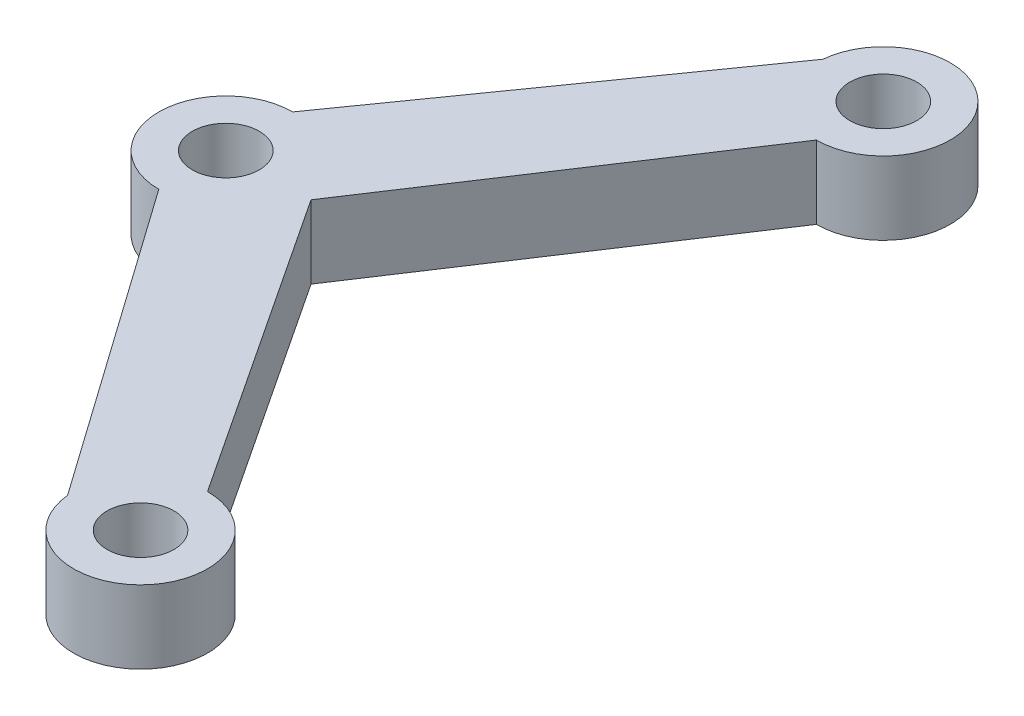
SolidWorks part; units mm, degrees
ref_plane "Front Plane" through (0, 0, 0) normal (0, 0, 1) x (1, 0, 0)
ref_plane "Top Plane" through (0, 0, 0) normal (0, 1, 0) x (1, 0, 0)
ref_plane "Right Plane" through (0, 0, 0) normal (1, 0, 0) x (0, 0, -1)
sketch "Sketch1" plane through (0, 0, 0) normal (0, 1, 0) x (1, 0, 0)
  line L1 (-15.25, -15.25) -> (15.25, -15.25) construction
  line L2 (-15.25, -15.25) -> (-15.25, 15.25) construction
  line L3 (-15.25, 15.25) -> (15.25, 15.25) construction
  line L4 (15.25, -15.25) -> (15.25, 15.25) construction
  line L5 (-15.25, -15.25) -> (15.25, 15.25) construction
  line L6 (-15.25, 15.25) -> (15.25, -15.25) construction
  point P0 (0, 0)
  dimension "D1" = 30.5
sketch "Sketch2" plane through (0, 0, 0) normal (0, 1, 0) x (1, 0, 0)
  line L1 (-23, -16) -> (23, -16) construction
  line L2 (-23, -16) -> (-23, 16) construction
  line L3 (-23, 16) -> (23, 16) construction
  line L4 (23, -16) -> (23, 16) construction
  line L5 (-23, -16) -> (23, 16) construction
  line L6 (-23, 16) -> (23, -16) construction
  line L7 (-23, 0) -> (23, 0) construction
  line L9 (-27, -2.75) -> (-17.9878, -15.509)
  line L10 (-15.25, -12.5) -> (-23.5, 0)
  line L11 (-15.25, 12.5) -> (-23.5, 0)
  line L12 (-17.9878, 15.509) -> (-27, 2.75)
  arc A0 (-27, 2.75) -> (-27, -2.75) centre (-27, 0) ccw
  circle A1 centre (-27, 0) radius 1.375
  circle A2 centre (-15.25, 15.25) radius 1.375
  arc A3 (-15.25, 12.5) -> (-17.9878, 15.509) centre (-15.25, 15.25) ccw
  circle A4 centre (-15.25, -15.25) radius 1.375
  arc A5 (-17.9878, -15.509) -> (-15.25, -12.5) centre (-15.25, -15.25) ccw
  point P0 (0, 0)
  dimension "D4" = 5.5
  dimension "D5" = 2.75
  dimension "D6" = 2.75
  dimension "D7" = 5.5
  dimension "D1" = 32
  dimension "D2" = 46
  dimension "D3" = 4
  dimension "D8" = 3.5
  dimension "D9" = 15.6209
extrude "Boss-Extrude1" add sketch "Sketch2" along normal blind 3
sketch "Sketch3" plane through (0, 3, 0) normal (0, 1, 0) x (1, 0, 0)
  circle A0 centre (-15.25, 15.25) radius 1.375
  circle A1 centre (-15.25, 15.25) radius 2.75
  circle A2 centre (-15.25, -15.25) radius 2.75
  circle A3 centre (-15.25, -15.25) radius 1.375
  dimension "D1" = 2.75
  dimension "D2" = 5.5
